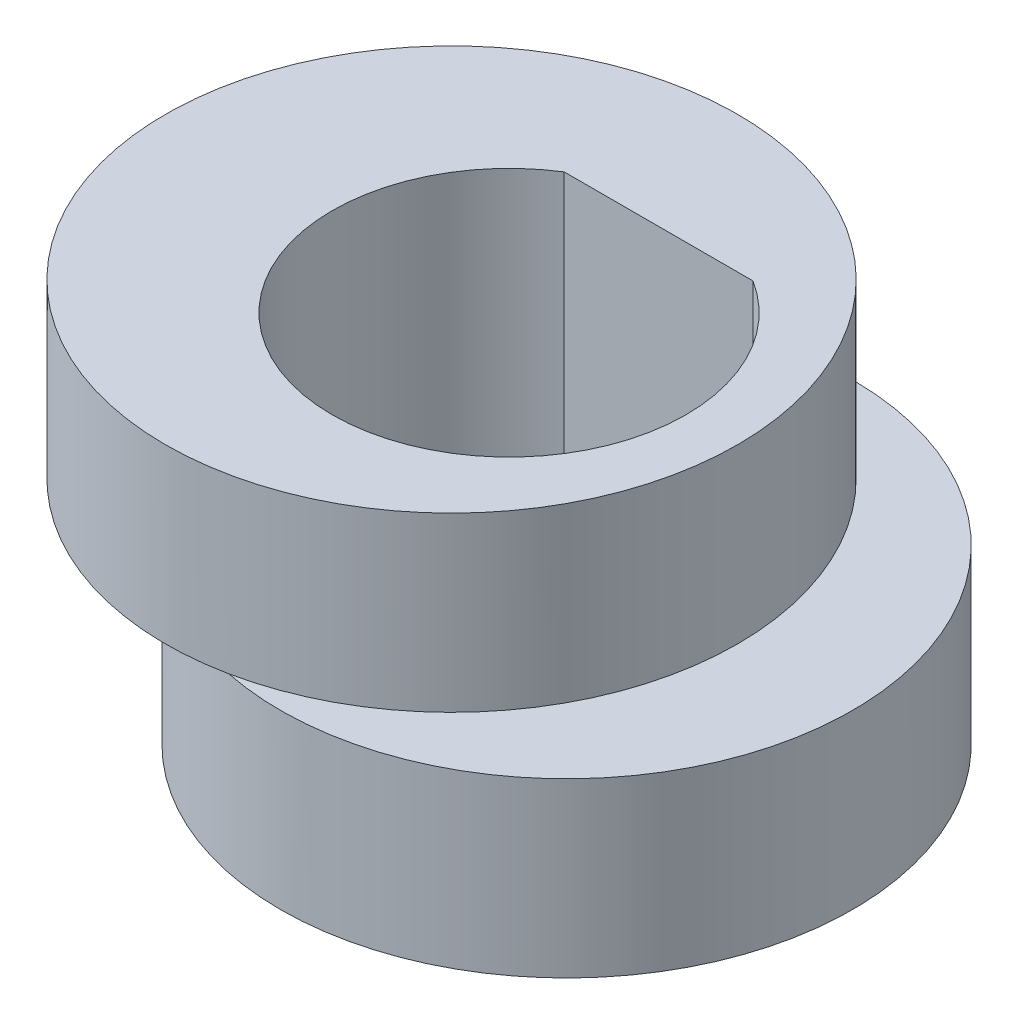
SolidWorks part; units mm, degrees
ref_plane "Alzado" through (0, 0, 0) normal (0, 0, 1) x (1, 0, 0)
ref_plane "Planta" through (0, 0, 0) normal (0, 1, 0) x (1, 0, 0)
ref_plane "Vista lateral" through (0, 0, 0) normal (1, 0, 0) x (0, 0, -1)
sketch "Croquis1" plane through (0, 0, 0) normal (0, 1, 0) x (1, 0, 0)
  circle A0 centre (1, 0) radius 4.975
  dimension "D1" = 9.95
  dimension "D2" = 1
extrude "Saliente-Extruir1" add sketch "Croquis1" along normal blind 3
sketch "Croquis2" plane through (0, 3, 0) normal (0, 1, 0) x (1, 0, 0)
  circle A0 centre (-1, 0) radius 4.975
  dimension "D1" = 9.95
  dimension "D2" = 1
extrude "Saliente-Extruir2" add sketch "Croquis2" along normal blind 3
sketch "Croquis3" plane through (0, 0, 0) normal (0, 1, 0) x (1, 0, 0)
  line L0 (-1.6418, 2.6) -> (1.6418, 2.6)
  arc A0 (-1.6418, 2.6) -> (1.6418, 2.6) centre (0, 0) ccw
  dimension "D1" = 6.15
  dimension "D2" = 2.6
extrude "Cortar-Extruir1" cut sketch "Croquis3" along normal through all
